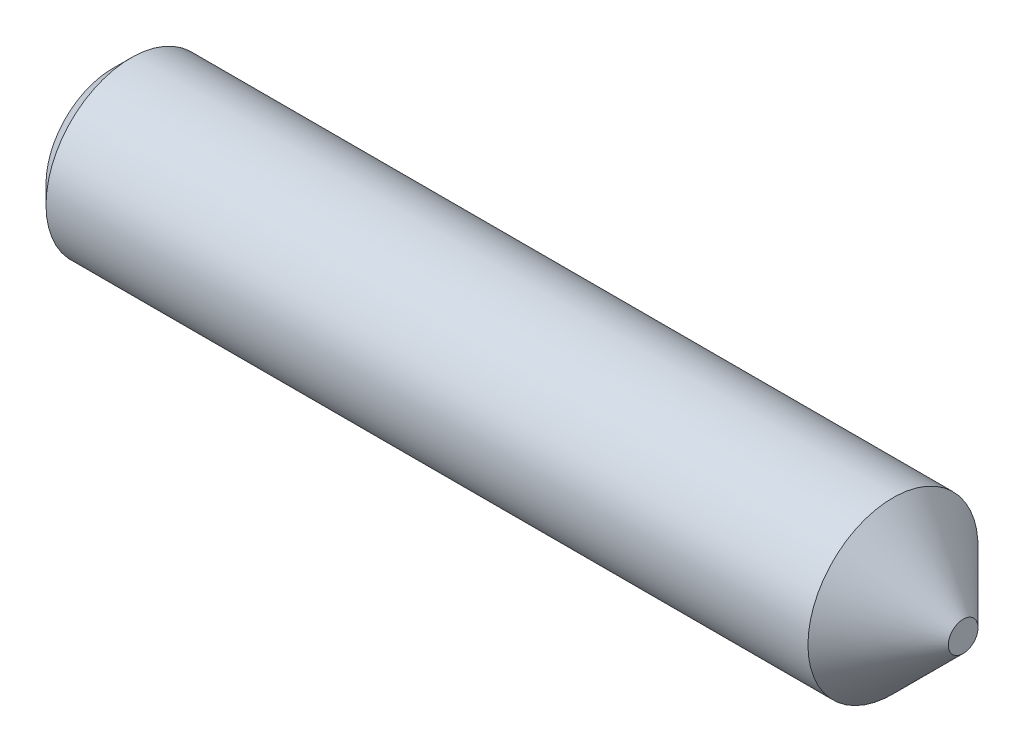
SolidWorks part; units mm, degrees
material "Stainless Steel (ferritic)"
ref_plane "Front Plane" through (0, 0, 0) normal (0, 0, 1) x (1, 0, 0)
ref_plane "Top Plane" through (0, 0, 0) normal (0, 1, 0) x (1, 0, 0)
ref_plane "Right Plane" through (0, 0, 0) normal (1, 0, 0) x (0, 0, -1)
sketch "Sketch1" plane through (0, 0, 0) normal (0, 0, 1) x (1, 0, 0)
  line L0 (0, 2) -> (0, 0)
  line L1 (0, 0) -> (20, 0)
  line L2 (20, 0) -> (20, 0.35)
  line L3 (20, 0.35) -> (18.35, 2)
  line L4 (18.35, 2) -> (0, 2)
  line L5 (0, 0) -> (20, 0) construction
revolve "Revolve1" add sketch "Sketch1" angle 360 about L5
sketch "Sketch2" plane through (0, 0, 0) normal (-1, 0, 0) x (0, 0, 1)
  line L0 (0.5774, 1) -> (-0.5774, 1)
  line L1 (-0.5774, 1) -> (-1.1547, 0)
  line L2 (-1.1547, 0) -> (-0.5774, -1)
  line L3 (-0.5774, -1) -> (0.5774, -1)
  line L4 (0.5774, -1) -> (1.1547, 0)
  line L5 (1.1547, 0) -> (0.5774, 1)
extrude "Cut-Extrude1" cut sketch "Sketch2" against normal blind 3.1667
chamfer "Chamfer1" distance 0.4295 angle 45 1 edges at (0, 0, -2)
